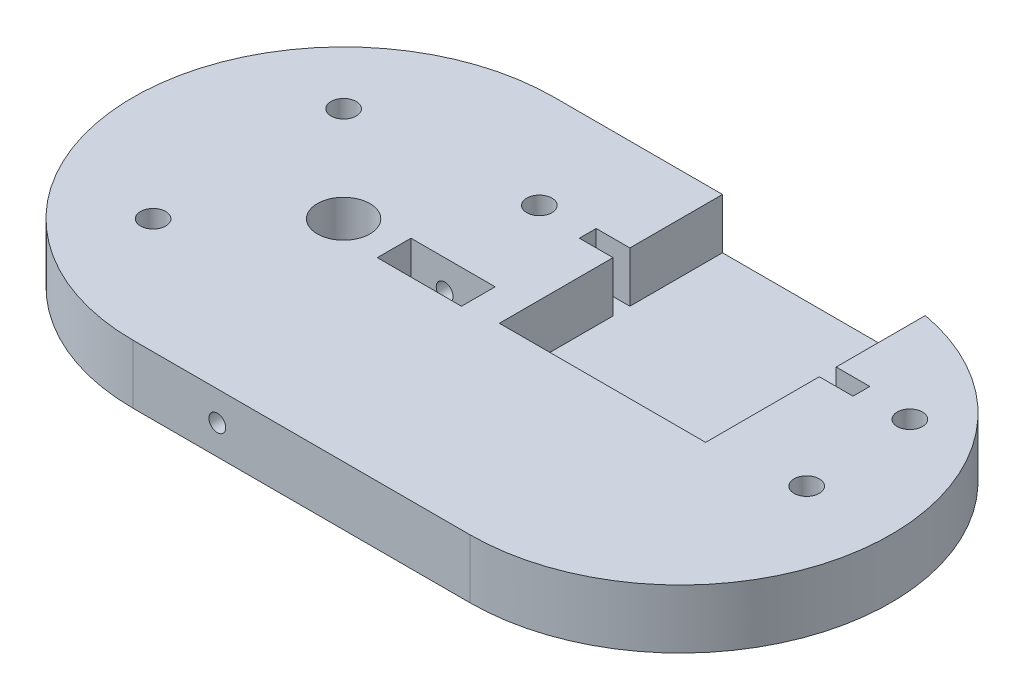
SolidWorks part; units mm, degrees
ref_plane "Plan de face" through (0, 0, 0) normal (0, 0, 1) x (1, 0, 0)
ref_plane "Plan de dessus" through (0, 0, 0) normal (0, 1, 0) x (1, 0, 0)
ref_plane "Plan de droite" through (0, 0, 0) normal (1, 0, 0) x (0, 0, -1)
sketch "Esquisse1" plane through (0, 0, 0) normal (0, 1, 0) x (1, 0, 0)
  line L0 (-71.6495, 25) -> (-31.6495, 25)
  line L1 (-31.6495, -25) -> (-71.6495, -25)
  arc A0 (-71.6495, -25) -> (-71.6495, 25) centre (-71.6495, 0) cw
  arc A1 (-31.6495, -25) -> (-31.6495, 25) centre (-31.6495, 0) ccw
  dimension "D1" = 25
  dimension "D2" = 40
extrude "Boss.-Extru.1" add sketch "Esquisse1" along normal blind 7
sketch "Esquisse2" plane through (0, 7, 0) normal (0, 1, 0) x (1, 0, 0)
  circle A0 centre (-71.6495, 0) radius 3.125
  dimension "D1" = 6.25
extrude "Enlèv. mat.-Extru.1" cut sketch "Esquisse2" against normal blind 7
sketch "Esquisse3" plane through (0, 7, 0) normal (0, 1, 0) x (1, 0, 0)
  line L0 (-51.6495, 30.5) -> (-27.1495, 30.5)
  line L1 (-27.1495, 30.5) -> (-27.1495, 14)
  line L2 (-27.1495, 14) -> (-23.1495, 14)
  line L3 (-23.1495, 14) -> (-23.1495, 12)
  line L4 (-23.1495, 12) -> (-27.1495, 12)
  line L5 (-27.1495, 12) -> (-27.1495, -1.5)
  line L6 (-27.1495, -1.5) -> (-51.6495, -1.5)
  line L7 (-51.6495, -1.5) -> (-51.6495, 12)
  line L8 (-51.6495, 12) -> (-55.6495, 12)
  line L9 (-55.6495, 12) -> (-55.6495, 14)
  line L10 (-55.6495, 14) -> (-51.6495, 14)
  line L11 (-51.6495, 14) -> (-51.6495, 30.5)
  line L12 (-71.6495, 0) -> (62.6843, 0) construction
  dimension "D1" = 2
  dimension "D2" = 2
  dimension "D3" = 24.5
  dimension "D4" = 32.5
  dimension "D5" = 16.5
  dimension "D6" = 13.5
  dimension "D7" = 1.5
  dimension "D8" = 20
extrude "Enlèv. mat.-Extru.2" cut sketch "Esquisse3" against normal blind 6
sketch "Esquisse4" plane through (0, 7, 0) normal (0, 1, 0) x (1, 0, 0)
  line L0 (-71.6495, 0) -> (-12.4598, 0) construction
  line L2 (-57.6495, -2) -> (-65.6495, -2)
  line L3 (-57.6495, -2) -> (-57.6495, 2)
  line L4 (-57.6495, 2) -> (-65.6495, 2)
  line L5 (-65.6495, -2) -> (-65.6495, 2)
  line L6 (-57.6495, -2) -> (-65.6495, 2) construction
  line L7 (-57.6495, 2) -> (-65.6495, -2) construction
  point P4 (-61.6495, 0)
  dimension "D1" = 4
  dimension "D2" = 8
  dimension "D3" = 10
extrude "Enlèv. mat.-Extru.3" cut sketch "Esquisse4" against normal up to next
chamfer "Chanfrein1" distance 2 angle 45 1 edges at (-57.6495, 7, 0)
sketch "Esquisse5" plane through (0, 0, 25) normal (0, 0, 1) x (1, 0, 0)
  line L0 (-61.6495, 7) -> (-61.6495, 0) construction
  line L1 (-71.6495, 7) -> (-31.6495, 7) construction
  line L2 (-71.6495, 0) -> (-31.6495, 0) construction
  line L3 (-71.6495, 7) -> (-71.6495, 0) construction
  circle A0 centre (-61.6495, 3.5) radius 1
  dimension "D1" = 2
  dimension "D2" = 10
extrude "Enlèv. mat.-Extru.4" cut sketch "Esquisse5" against normal through all
sketch "Esquisse7" plane through (0, 7, 0) normal (0, 1, 0) x (1, 0, 0)
  line L0 (-71.6495, 0) -> (-16.6495, 0) construction
  line L1 (-71.6495, 0) -> (-92.1707, 20.5213) construction
  line L2 (-71.6495, 0) -> (-93.1594, -21.5099) construction
  line L3 (-5.3452, 13) -> (-66.7258, 13) construction
  line L7 (-23.1495, 14) -> (-27.1495, 14) construction
  line L8 (-51.6495, 14) -> (-51.6495, 25) construction
  circle A0 centre (-16.6495, 0) radius 1.5
  circle A1 centre (-82.9632, 11.3137) radius 1.5
  circle A2 centre (-82.9632, -11.3137) radius 1.5
  circle A3 centre (-61.3995, 13) radius 1.5
  circle A4 centre (-17.3995, 13) radius 1.5
  point P18 (-39.3995, 13)
  dimension "D1" = 3
  dimension "D2" = 3
  dimension "D3" = 3
  dimension "D10" = 3
  dimension "D11" = 3
  dimension "D4" = 90
  dimension "D5" = 135
  dimension "D6" = 16
  dimension "D7" = 16
  dimension "D8" = 55
  dimension "D9" = 1
  dimension "D12" = 12.25
  dimension "D13" = 22
  dimension "D14" = 22
extrude "Enlèv. mat.-Extru.6" cut sketch "Esquisse7" against normal blind 8
